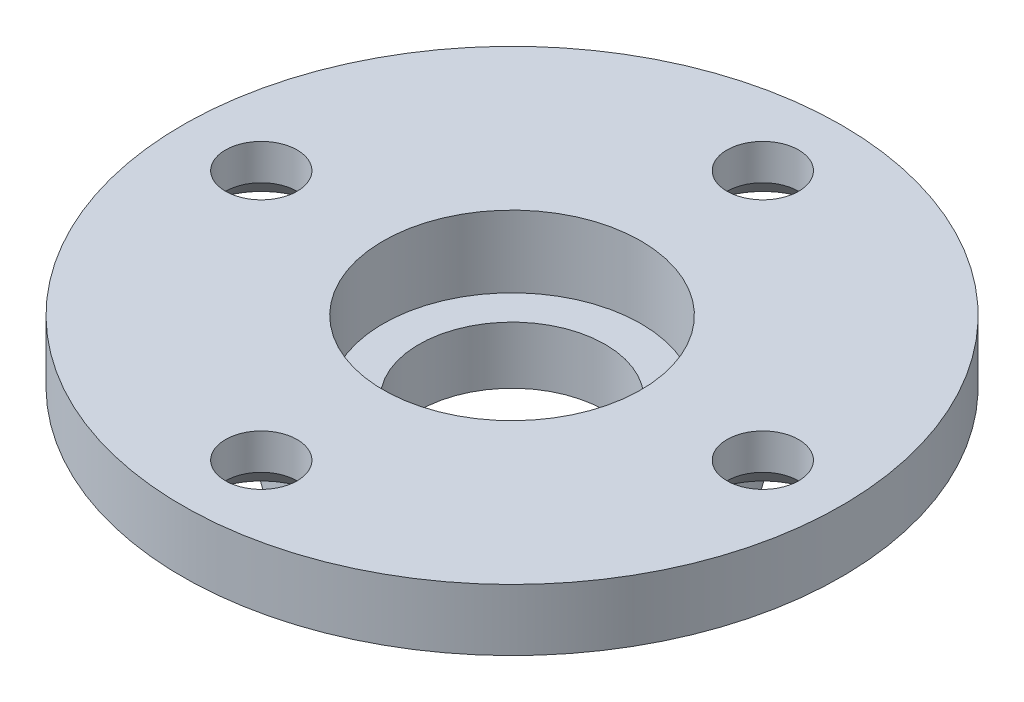
SolidWorks part; units mm, degrees
ref_plane "Piano frontale" through (0, 0, 0) normal (0, 0, 1) x (1, 0, 0)
ref_plane "Piano superiore" through (0, 0, 0) normal (0, 1, 0) x (1, 0, 0)
ref_plane "Piano destro" through (0, 0, 0) normal (1, 0, 0) x (0, 0, -1)
sketch "Schizzo1" plane through (0, 0, 0) normal (0, 0, 1) x (1, 0, 0)
  line L0 (0, 0) -> (0, 10) construction
  line L1 (6.5, 0) -> (6.5, 4)
  line L2 (6.5, 4) -> (9, 4)
  line L3 (9, 4) -> (9, 9)
  line L4 (9, 9) -> (23, 9)
  line L11 (23, 9) -> (23, 4.7)
  line L12 (23, 4.7) -> (12.5, 4.7)
  line L13 (12.5, 4.7) -> (12.5, 0)
  line L14 (6.5, 0) -> (12.5, 0)
  dimension "D1" = 13
  dimension "D2" = 18
  dimension "D3" = 25
  dimension "D4" = 5
  dimension "D5" = 9
  dimension "D6" = 4.3
revolve "Rivoluzione1" add sketch "Schizzo1" angle 360 about L0
sketch "Schizzo2" plane through (0, 4.7, 0) normal (0, -1, 0) x (1, 0, 0)
  circle A0 centre (0, 0) radius 17.5
  dimension "D1" = 35
hole_wizard "Foro svasato per Vite M5-1" positions "Schizzo3" profile "Schizzo4" countersink size "M5" standard "ISO" end condition up to next
sketch "Schizzo3" plane through (0, 4.7, 0) normal (0, -1, 0) x (-1, 0, 0)
  line L0 (0, 0) -> (-17.5, 0) construction
  circle A0 centre (0, 0) radius 17.5 construction
  point P1 (-17.5, 0)
sketch "Schizzo4" plane through (17.5, 4.7, 0) normal (1, 0, 0) x (0, 0, -1)
  line L0 (0, 0) -> (0, 4.3)
  line L1 (0, 4.3) -> (2.5, 4.3)
  line L2 (2.5, 4.3) -> (2.5, 1.8)
  line L3 (2.5, 1.8) -> (4.3, 0)
  line L5 (4.3, 0) -> (0, 0)
  line L6 (-2.5, 1.8) -> (-4.3, 0) construction
  line L11 (0, -6.35) -> (0, 107.95) construction
  dimension "Thru Hole Dia." = 5
  dimension "Thru Hole Depth" = 4.3
  dimension "Near C'Sink Dia." = 8.6
  dimension "Near C'Sink Angle" = 90
pattern_circular "RipetizioneCircolare1" count 4 over 360 about axis through (0, 0, 0) along (0, 1, 0) of "Foro svasato per Vite M5-1"
